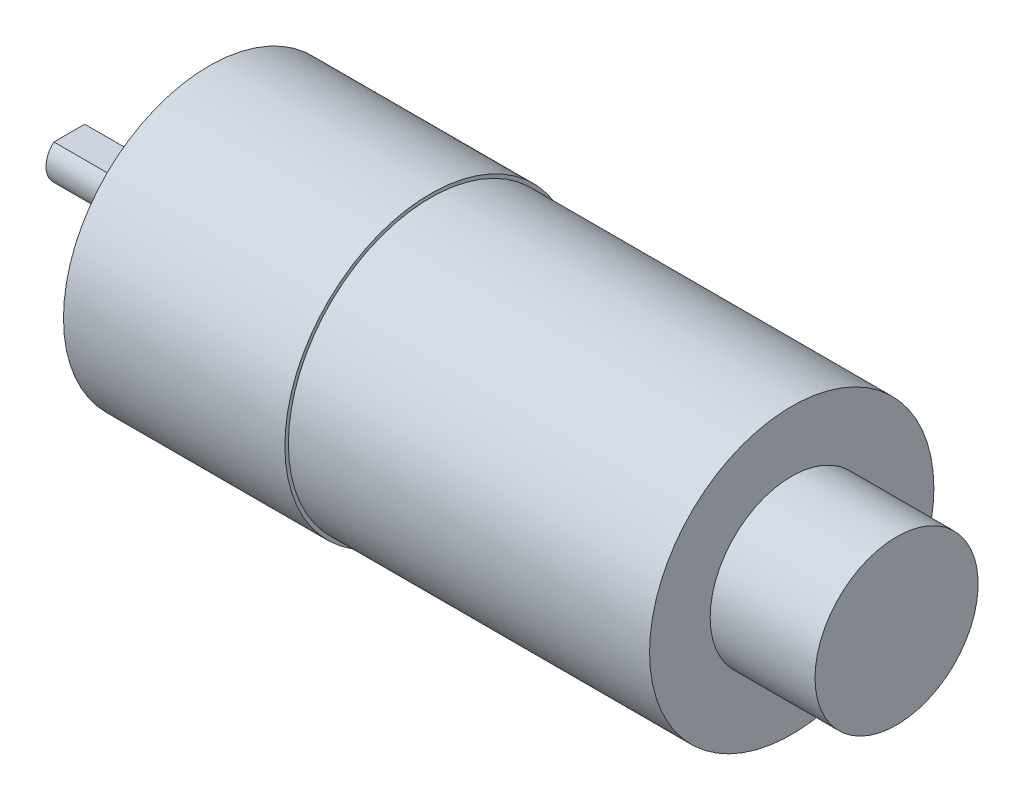
SolidWorks part; units mm, degrees
ref_plane "Front Plane" through (0, 0, 0) normal (0, 0, 1) x (1, 0, 0)
ref_plane "Top Plane" through (0, 0, 0) normal (0, 1, 0) x (1, 0, 0)
ref_plane "Right Plane" through (0, 0, 0) normal (1, 0, 0) x (0, 0, -1)
sketch "Sketch1" plane through (0, 0, 0) normal (0, 0, 1) x (1, 0, 0)
  line L0 (0, 0) -> (69.9216, 0) construction
  line L1 (0, 0) -> (0, 3.5)
  line L2 (0, 3.5) -> (2.5, 3.5)
  line L3 (2.5, 3.5) -> (2.5, 12.5)
  line L4 (2.5, 12.5) -> (21.5, 12.5)
  line L5 (21.5, 12.5) -> (21.5, 0)
  line L6 (0, 2) -> (-9.5, 2)
  line L7 (-9.5, 2) -> (-9.5, 0)
  line L8 (-9.5, 0) -> (0, 0)
  line L9 (21.5, 12.2) -> (52.5, 12.2)
  line L10 (52.5, 12.2) -> (52.5, 0)
  line L11 (52.5, 7) -> (61.5, 7)
  line L12 (61.5, 7) -> (61.5, 0)
  dimension "D1" = 3.5
  dimension "D2" = 2
  dimension "D3" = 12.5
  dimension "D4" = 12.2
  dimension "D5" = 31
  dimension "D6" = 19
  dimension "D7" = 2.5
  dimension "D8" = 12
  dimension "D9" = 7
  dimension "D10" = 9
revolve "Revolve1" add sketch "Sketch1" angle 360 about L0
sketch "Sketch2" plane through (-9.5, 0, 0) normal (-1, 0, 0) x (0, 0, 1)
  line L0 (0, -2) -> (0, 2) construction
  line L1 (2, 1.5) -> (-2, 1.5)
  line L2 (-2, 1.5) -> (-2, 2)
  line L3 (-2, 2) -> (2, 2)
  line L4 (2, 1.5) -> (2, 2)
  circle A0 centre (0, 0) radius 2 construction
  point P10 (0, 1.5)
  dimension "D1" = 4
  dimension "D2" = 3.5
extrude "Cut-Extrude1" cut sketch "Sketch2" against normal blind 8
sketch "Sketch3" plane through (2.5, 0, 0) normal (-1, 0, 0) x (0, 0, 1)
  line L0 (0, 0) -> (10.2868, 0) construction
  line L1 (0, 0) -> (0, 8.5) construction
  circle A0 centre (0, 8.5) radius 1.25
  circle A1 centre (0, -8.5) radius 1.25
  dimension "D2" = 2.5
  dimension "D1" = 8.5
extrude "Cut-Extrude2" cut sketch "Sketch3" against normal blind 8
